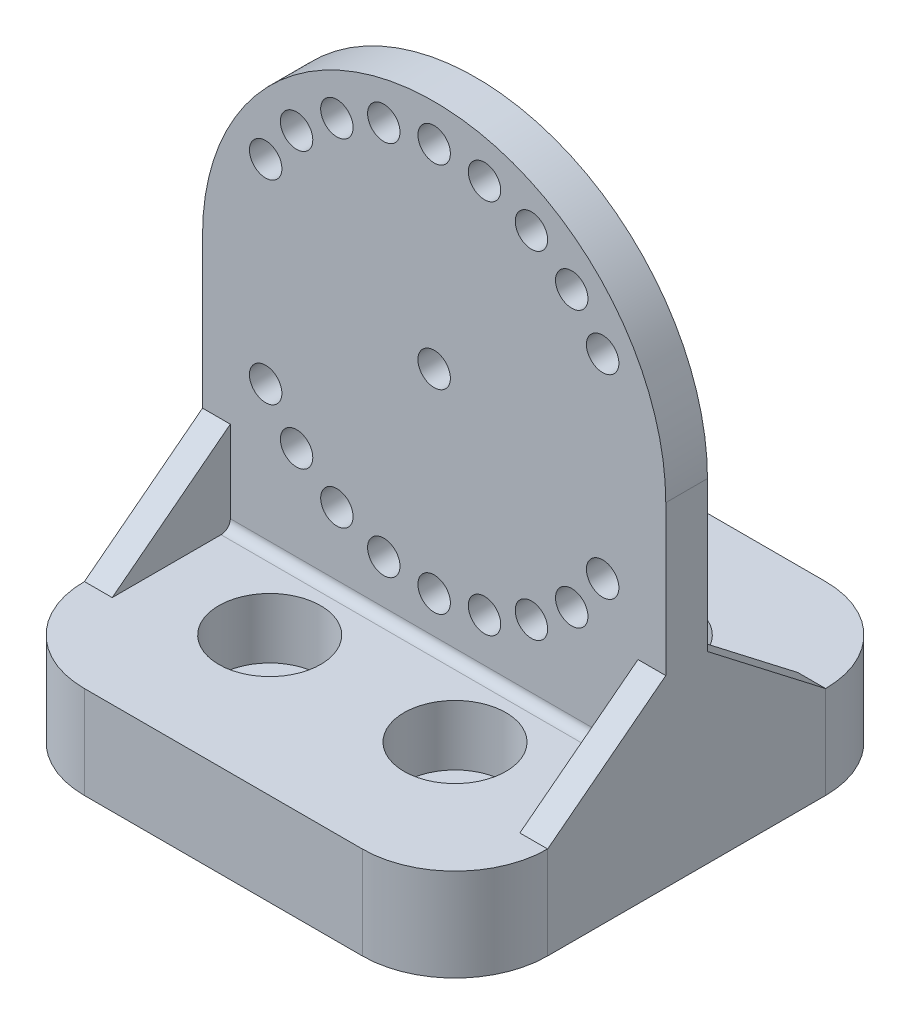
SolidWorks part; units mm, degrees
ref_plane "正面" through (0, 0, 0) normal (0, 0, 1) x (1, 0, 0)
ref_plane "平面" through (0, 0, 0) normal (0, 1, 0) x (1, 0, 0)
ref_plane "右側面" through (0, 0, 0) normal (1, 0, 0) x (0, 0, -1)
sketch "ｽｹｯﾁ1" plane through (0, 0, 0) normal (0, 1, 0) x (1, 0, 0)
  line L1 (25, 25) -> (-25, 25)
  line L2 (25, 25) -> (25, -25)
  line L3 (25, -25) -> (-25, -25)
  line L4 (-25, 25) -> (-25, -25)
  line L5 (25, 25) -> (-25, -25) construction
  line L6 (25, -25) -> (-25, 25) construction
  point P0 (0, 0)
  dimension "D1" = 50
  dimension "D2" = 50
extrude "ﾎﾞｽ - 押し出し1" add sketch "ｽｹｯﾁ1" along normal blind 10
sketch "ｽｹｯﾁ2" plane through (0, 0, 0) normal (0, 0, 1) x (1, 0, 0)
  line L0 (25, 10) -> (-25, 10)
  line L1 (-25, 10) -> (25, 10)
  line L4 (-25, 36) -> (-25, 10)
  line L5 (-25, 10) -> (25, 10)
  line L6 (-12, 10) -> (6.5, 10)
  line L7 (-25, 10) -> (25, 10)
  line L8 (25, 36) -> (25, 10)
  arc A1 (25, 36) -> (-25, 36) centre (0, 36) ccw
  circle A2 centre (0, 36) radius 1.75
  dimension "D1" = 26
  dimension "D3" = 0
  dimension "D2" = 25
  dimension "D6" = 3.5
  dimension "D4" = 26
  dimension "D5" = 26
extrude "ﾎﾞｽ - 押し出し2" add sketch "ｽｹｯﾁ2" along normal mid plane 4.5 contours L8 A1 L4 L0 L5
sketch "ｽｹｯﾁ5" plane through (0, 0, 0) normal (0, 0, 1) x (1, 0, 0)
  circle A0 centre (0, 36) radius 21
  circle A1 centre (0, 57) radius 1.75
  circle A2 centre (5.4352, 56.2844) radius 1.75
  circle A3 centre (10.5, 54.1865) radius 1.75
  circle A4 centre (14.8492, 50.8492) radius 1.75
  circle A5 centre (18.1865, 46.5) radius 1.75
  circle A6 centre (20.2844, 41.4352) radius 1.75
  circle A7 centre (21, 36) radius 1.75
  circle A8 centre (20.2844, 30.5648) radius 1.75
  circle A9 centre (18.1865, 25.5) radius 1.75
  circle A10 centre (14.8492, 21.1508) radius 1.75
  circle A11 centre (10.5, 17.8135) radius 1.75
  circle A12 centre (5.4352, 15.7156) radius 1.75
  circle A13 centre (0, 15) radius 1.75
  circle A14 centre (-5.4352, 15.7156) radius 1.75
  circle A15 centre (-10.5, 17.8135) radius 1.75
  circle A16 centre (-14.8492, 21.1508) radius 1.75
  circle A17 centre (-18.1865, 25.5) radius 1.75
  circle A18 centre (-20.2844, 30.5648) radius 1.75
  circle A19 centre (-21, 36) radius 1.75
  circle A20 centre (-20.2844, 41.4352) radius 1.75
  circle A21 centre (-18.1865, 46.5) radius 1.75
  circle A22 centre (-14.8492, 50.8492) radius 1.75
  circle A23 centre (-10.5, 54.1865) radius 1.75
  circle A24 centre (-5.4352, 56.2844) radius 1.75
  point P54 (0, 36)
  dimension "D1" = 42
  dimension "D2" = 3.5
  dimension "D3" = 24
  dimension "D4" = 0
  dimension "D5" = 0
extrude "ｶｯﾄ - 押し出し1" cut sketch "ｽｹｯﾁ5" against normal through all both and the other way through all contours A1 | A24 | A23 | A22 | A21 | A2 | A3 | A4 | A5 | A13 | A14 | A15 | A16 | A12 | A11 | A10 | A9 | A17
sketch "ｽｹｯﾁ6" plane through (0, 0, 0) normal (0, 1, 0) x (1, 0, 0)
  line L0 (0, -25) -> (0, 25) construction
  line L1 (-25, -25) -> (25, -25) construction
  line L2 (25, 25) -> (-25, 25) construction
  line L3 (-25, 0) -> (25, 0) construction
  line L4 (-25, 25) -> (-25, -25) construction
  line L5 (25, -25) -> (25, 25) construction
  circle A0 centre (-10, -10) radius 3.3
  circle A1 centre (10, -10) radius 3.3
  circle A2 centre (10, 10) radius 3.3
  circle A3 centre (-10, 10) radius 3.3
  dimension "D1" = 6.6
  dimension "D2" = 10
  dimension "D3" = 10
extrude "ｶｯﾄ - 押し出し3" cut sketch "ｽｹｯﾁ6" against normal blind 5 and the other way through all
fillet "ﾌｨﾚｯﾄ1" radius 10 4 edges at (-25, 5, 25) (-25, 5, -25) (25, 5, -25) (25, 5, 25)
sketch "ｽｹｯﾁ8" plane through (0, 10, 0) normal (0, 1, 0) x (1, 0, 0)
  line L0 (-25, 0) -> (25, 0) construction
  line L1 (-25, -2.25) -> (-25, 2.25) construction
  line L2 (25, -2.25) -> (25, 2.25) construction
  line L3 (0, 25) -> (0, -25) construction
  line L4 (15, 25) -> (-15, 25) construction
  line L5 (-15, -25) -> (15, -25) construction
  circle A0 centre (-10, -10) radius 5.5
  circle A1 centre (10, -10) radius 5.5
  circle A2 centre (10, 10) radius 5.5
  circle A3 centre (-10, 10) radius 5.5
  dimension "D1" = 11
extrude "ｶｯﾄ - 押し出し5" cut sketch "ｽｹｯﾁ8" against normal blind 6.5
sketch "ｽｹｯﾁ10" plane through (0, 0, 2.25) normal (0, 0, 1) x (1, 0, 0)
  line L0 (0, 36) -> (12.5, 14.3494)
  line L1 (0, 36) -> (25, 36)
  line L2 (12.5, 14.3494) -> (25, 21.5662)
  line L4 (25, 36) -> (25, 10) construction
  line L5 (0, 36) -> (0, 10) construction
  line L6 (25, 10) -> (22, 10)
  line L7 (25, 10) -> (25, 19.8342)
  line L8 (25, 19.8342) -> (22, 19.8342)
  line L9 (22, 10) -> (22, 19.8342)
  line L10 (25, 10) -> (-25, 10) construction
  line L11 (-22, 10) -> (-22, 19.8342)
  line L12 (-25, 10) -> (-22, 10)
  line L13 (-25, 10) -> (-25, 19.8342)
  line L14 (-25, 19.8342) -> (-22, 19.8342)
  line L15 (-12.5, 14.3494) -> (-25, 21.5662)
  circle A0 centre (0, 36) radius 25
  dimension "D1" = 50
  dimension "D2" = 60
  dimension "D3" = 90
  dimension "D4" = 3
sketch "ｽｹｯﾁ11" plane through (25, 0, 0) normal (1, 0, 0) x (0, 0, -1)
  line L0 (-2.25, 19.8342) -> (-15, 10)
  line L1 (-15, 10) -> (-2.25, 10)
  line L2 (-2.25, 10) -> (-2.25, 19.8342)
  line L3 (0, 0) -> (0, 36) construction
  line L4 (-15, 0) -> (15, 0) construction
  line L5 (-2.25, 36) -> (2.25, 36) construction
  line L6 (15, 10) -> (2.25, 10)
  line L7 (2.25, 10) -> (2.25, 19.8342)
  line L8 (2.25, 19.8342) -> (15, 10)
extrude "ﾎﾞｽ - 押し出し3" add sketch "ｽｹｯﾁ11" against normal blind 3
sketch "ｽｹｯﾁ12" plane through (-25, 0, 0) normal (-1, 0, 0) x (0, 0, 1)
  line L0 (2.25, 19.8342) -> (15, 10)
  line L1 (2.25, 10) -> (15, 10) construction
  line L2 (15, 0) -> (15, 10) construction
  line L3 (0, 0) -> (0, 36) construction
  line L4 (-15, 0) -> (15, 0) construction
  line L5 (2.25, 36) -> (-2.25, 36) construction
  line L6 (-2.25, 19.8342) -> (-15, 10)
  line L7 (-2.25, 19.8342) -> (-2.25, 10)
  line L8 (-2.25, 10) -> (-15, 10)
  line L9 (15, 10) -> (2.25, 10)
  line L10 (2.25, 10) -> (2.25, 19.8342)
extrude "ﾎﾞｽ - 押し出し4" add sketch "ｽｹｯﾁ12" against normal blind 3
fillet "ﾌｨﾚｯﾄ2" radius 1 2 edges
